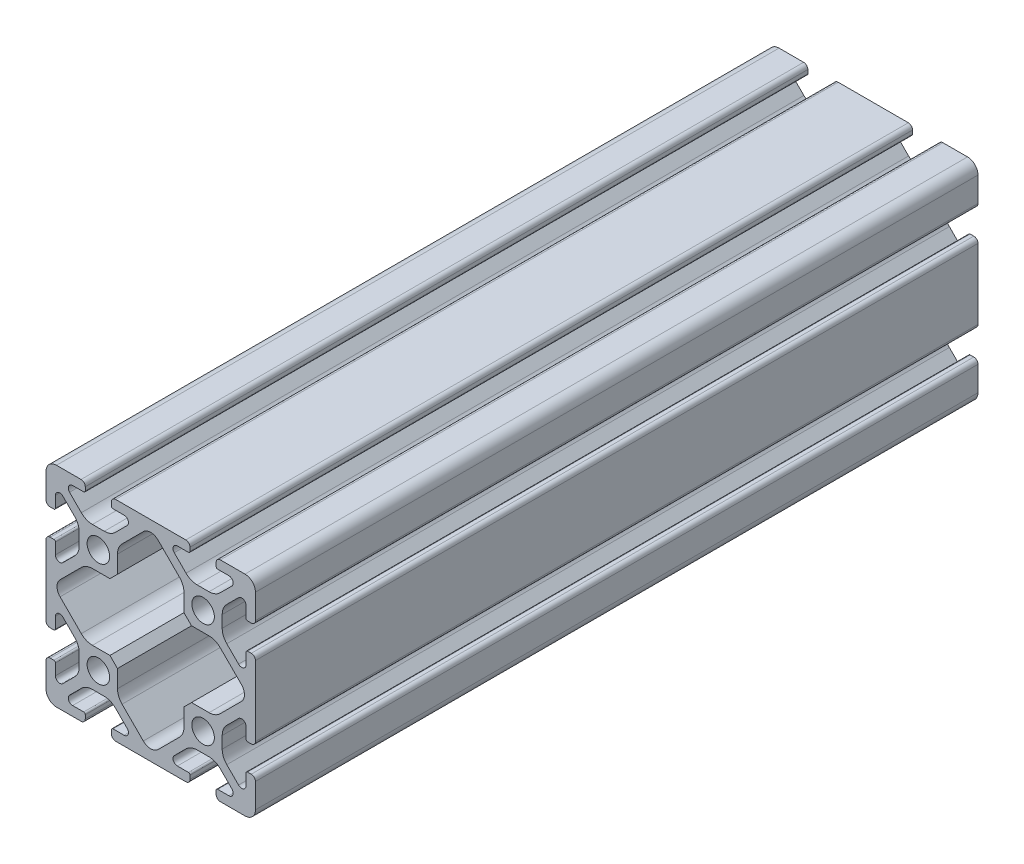
SolidWorks part; units mm, degrees
material "Alliage 1060"
ref_plane "Plan de face" through (0, 0, 0) normal (0, 0, 1) x (1, 0, 0)
ref_plane "Plan de dessus" through (0, 0, 0) normal (0, 1, 0) x (1, 0, 0)
ref_plane "Plan de droite" through (0, 0, 0) normal (1, 0, 0) x (0, 0, -1)
ref_plane "Plan1" through (0, 0, 0) normal (0, 0, -1) x (-1, 0, 0)
sketch "Esquisse1" plane through (0, 0, 0) normal (0, 0, -1) x (-1, 0, 0)
  line L0 (0, 13.3) -> (0, 26.7)
  line L1 (-0.8, 27.5) -> (-1.5, 27.5)
  line L2 (-1.8, 27.2) -> (-1.8, 25.0816)
  line L3 (-3.2196, 24.4936) -> (-5.4713, 26.7453)
  line L4 (-6.35, 28.8666) -> (-6.35, 31.1334)
  line L5 (-5.4713, 33.2547) -> (-3.2196, 35.5064)
  line L6 (-1.8, 34.9184) -> (-1.8, 32.8)
  line L7 (-1.5, 32.5) -> (-0.8, 32.5)
  line L8 (0, 33.3) -> (0, 38)
  line L9 (-2, 40) -> (-6.7, 40)
  line L10 (-7.5, 39.2) -> (-7.5, 38.5)
  line L11 (-7.2, 38.2) -> (-5.0816, 38.2)
  line L12 (-4.4936, 36.7804) -> (-6.7453, 34.5287)
  line L13 (-8.8666, 33.65) -> (-11.1334, 33.65)
  line L14 (-13.2547, 34.5287) -> (-15.5064, 36.7804)
  line L15 (-14.9184, 38.2) -> (-12.8, 38.2)
  line L16 (-12.5, 38.5) -> (-12.5, 39.2)
  line L17 (-13.3, 40) -> (-26.7, 40)
  line L18 (-27.5, 39.2) -> (-27.5, 38.5)
  line L19 (-27.2, 38.2) -> (-25.0816, 38.2)
  line L20 (-24.4936, 36.7804) -> (-26.7453, 34.5287)
  line L21 (-28.8666, 33.65) -> (-31.1334, 33.65)
  line L22 (-33.2547, 34.5287) -> (-35.5064, 36.7804)
  line L23 (-34.9184, 38.2) -> (-32.8, 38.2)
  line L24 (-32.5, 38.5) -> (-32.5, 39.2)
  line L25 (-33.3, 40) -> (-38, 40)
  line L26 (-40, 38) -> (-40, 33.3)
  line L27 (-39.2, 32.5) -> (-38.5, 32.5)
  line L28 (-38.2, 32.8) -> (-38.2, 34.9184)
  line L29 (-36.7804, 35.5064) -> (-34.5287, 33.2547)
  line L30 (-33.65, 31.1334) -> (-33.65, 28.8666)
  line L31 (-34.5287, 26.7453) -> (-36.7804, 24.4936)
  line L32 (-38.2, 25.0816) -> (-38.2, 27.2)
  line L33 (-38.5, 27.5) -> (-39.2, 27.5)
  line L34 (-40, 26.7) -> (-40, 13.3)
  line L35 (-39.2, 12.5) -> (-38.5, 12.5)
  line L36 (-38.2, 12.8) -> (-38.2, 14.9184)
  line L37 (-36.7804, 15.5064) -> (-34.5287, 13.2547)
  line L38 (-33.65, 11.1334) -> (-33.65, 8.8666)
  line L39 (-34.5287, 6.7453) -> (-36.7804, 4.4936)
  line L40 (-38.2, 5.0816) -> (-38.2, 7.2)
  line L41 (-38.5, 7.5) -> (-39.2, 7.5)
  line L42 (-40, 6.7) -> (-40, 2)
  line L43 (-38, 0) -> (-33.3, 0)
  line L44 (-32.5, 0.8) -> (-32.5, 1.5)
  line L45 (-32.8, 1.8) -> (-34.9184, 1.8)
  line L46 (-35.5064, 3.2196) -> (-33.2547, 5.4713)
  line L47 (-31.1334, 6.35) -> (-28.8666, 6.35)
  line L48 (-26.7453, 5.4713) -> (-24.4936, 3.2196)
  line L49 (-25.0816, 1.8) -> (-27.2, 1.8)
  line L50 (-27.5, 1.5) -> (-27.5, 0.8)
  line L51 (-26.7, 0) -> (-13.3, 0)
  line L52 (-12.5, 0.8) -> (-12.5, 1.5)
  line L53 (-12.8, 1.8) -> (-14.9184, 1.8)
  line L54 (-15.5064, 3.2196) -> (-13.2547, 5.4713)
  line L55 (-11.1334, 6.35) -> (-8.8666, 6.35)
  line L56 (-6.7453, 5.4713) -> (-4.4936, 3.2196)
  line L57 (-5.0816, 1.8) -> (-7.2, 1.8)
  line L58 (-7.5, 1.5) -> (-7.5, 0.8)
  line L59 (-6.7, 0) -> (-2, 0)
  line L60 (0, 2) -> (0, 6.7)
  line L61 (-0.8, 7.5) -> (-1.5, 7.5)
  line L62 (-1.8, 7.2) -> (-1.8, 5.0816)
  line L63 (-3.2196, 4.4936) -> (-5.4713, 6.7453)
  line L64 (-6.35, 8.8666) -> (-6.35, 11.1334)
  line L65 (-5.4713, 13.2547) -> (-3.2196, 15.5064)
  line L66 (-1.8, 14.9184) -> (-1.8, 12.8)
  line L67 (-1.5, 12.5) -> (-0.8, 12.5)
  line L68 (-12.2079, 13.65) -> (-13.65, 12.2079)
  line L69 (-13.65, 12.2079) -> (-13.65, 8.8654)
  line L70 (-14.5287, 6.7441) -> (-18.5858, 2.687)
  line L71 (-21.4142, 2.687) -> (-25.4713, 6.7441)
  line L72 (-26.35, 8.8654) -> (-26.35, 12.2079)
  line L73 (-26.35, 12.2079) -> (-27.0711, 12.9289)
  line L74 (-27.0711, 12.9289) -> (-27.7921, 13.65)
  line L75 (-27.7921, 13.65) -> (-31.1346, 13.65)
  line L76 (-33.2559, 14.5287) -> (-37.313, 18.5858)
  line L77 (-37.313, 21.4142) -> (-33.2559, 25.4713)
  line L78 (-31.1346, 26.35) -> (-27.7921, 26.35)
  line L79 (-27.7921, 26.35) -> (-27.0711, 27.0711)
  line L80 (-27.0711, 27.0711) -> (-26.35, 27.7921)
  line L81 (-26.35, 27.7921) -> (-26.35, 31.1346)
  line L82 (-25.4713, 33.2559) -> (-21.4142, 37.313)
  line L83 (-18.5858, 37.313) -> (-14.5287, 33.2559)
  line L84 (-13.65, 31.1346) -> (-13.65, 27.7921)
  line L85 (-13.65, 27.7921) -> (-12.2079, 26.35)
  line L86 (-12.2079, 26.35) -> (-8.8654, 26.35)
  line L87 (-6.7441, 25.4713) -> (-2.687, 21.4142)
  line L88 (-2.687, 18.5858) -> (-6.7441, 14.5287)
  line L89 (-8.8654, 13.65) -> (-12.2079, 13.65)
  arc A0 (-0.8, 12.5) -> (0, 13.3) centre (-0.8, 13.3) ccw
  arc A1 (0, 26.7) -> (-0.8, 27.5) centre (-0.8, 26.7) ccw
  arc A2 (-1.5, 27.5) -> (-1.8, 27.2) centre (-1.5, 27.2) ccw
  arc A3 (-1.8, 25.0816) -> (-3.2196, 24.4936) centre (-2.6316, 25.0816) cw
  arc A4 (-5.4713, 26.7453) -> (-6.35, 28.8666) centre (-3.35, 28.8666) cw
  arc A5 (-6.35, 31.1334) -> (-5.4713, 33.2547) centre (-3.35, 31.1334) cw
  arc A6 (-3.2196, 35.5064) -> (-1.8, 34.9184) centre (-2.6316, 34.9184) cw
  arc A7 (-1.8, 32.8) -> (-1.5, 32.5) centre (-1.5, 32.8) ccw
  arc A8 (-0.8, 32.5) -> (0, 33.3) centre (-0.8, 33.3) ccw
  arc A9 (0, 38) -> (-2, 40) centre (-2, 38) ccw
  arc A10 (-6.7, 40) -> (-7.5, 39.2) centre (-6.7, 39.2) ccw
  arc A11 (-7.5, 38.5) -> (-7.2, 38.2) centre (-7.2, 38.5) ccw
  arc A12 (-5.0816, 38.2) -> (-4.4936, 36.7804) centre (-5.0816, 37.3684) cw
  arc A13 (-6.7453, 34.5287) -> (-8.8666, 33.65) centre (-8.8666, 36.65) cw
  arc A14 (-11.1334, 33.65) -> (-13.2547, 34.5287) centre (-11.1334, 36.65) cw
  arc A15 (-15.5064, 36.7804) -> (-14.9184, 38.2) centre (-14.9184, 37.3684) cw
  arc A16 (-12.8, 38.2) -> (-12.5, 38.5) centre (-12.8, 38.5) ccw
  arc A17 (-12.5, 39.2) -> (-13.3, 40) centre (-13.3, 39.2) ccw
  arc A18 (-26.7, 40) -> (-27.5, 39.2) centre (-26.7, 39.2) ccw
  arc A19 (-27.5, 38.5) -> (-27.2, 38.2) centre (-27.2, 38.5) ccw
  arc A20 (-25.0816, 38.2) -> (-24.4936, 36.7804) centre (-25.0816, 37.3684) cw
  arc A21 (-26.7453, 34.5287) -> (-28.8666, 33.65) centre (-28.8666, 36.65) cw
  arc A22 (-31.1334, 33.65) -> (-33.2547, 34.5287) centre (-31.1334, 36.65) cw
  arc A23 (-35.5064, 36.7804) -> (-34.9184, 38.2) centre (-34.9184, 37.3684) cw
  arc A24 (-32.8, 38.2) -> (-32.5, 38.5) centre (-32.8, 38.5) ccw
  arc A25 (-32.5, 39.2) -> (-33.3, 40) centre (-33.3, 39.2) ccw
  arc A26 (-38, 40) -> (-40, 38) centre (-38, 38) ccw
  arc A27 (-40, 33.3) -> (-39.2, 32.5) centre (-39.2, 33.3) ccw
  arc A28 (-38.5, 32.5) -> (-38.2, 32.8) centre (-38.5, 32.8) ccw
  arc A29 (-38.2, 34.9184) -> (-36.7804, 35.5064) centre (-37.3684, 34.9184) cw
  arc A30 (-34.5287, 33.2547) -> (-33.65, 31.1334) centre (-36.65, 31.1334) cw
  arc A31 (-33.65, 28.8666) -> (-34.5287, 26.7453) centre (-36.65, 28.8666) cw
  arc A32 (-36.7804, 24.4936) -> (-38.2, 25.0816) centre (-37.3684, 25.0816) cw
  arc A33 (-38.2, 27.2) -> (-38.5, 27.5) centre (-38.5, 27.2) ccw
  arc A34 (-39.2, 27.5) -> (-40, 26.7) centre (-39.2, 26.7) ccw
  arc A35 (-40, 13.3) -> (-39.2, 12.5) centre (-39.2, 13.3) ccw
  arc A36 (-38.5, 12.5) -> (-38.2, 12.8) centre (-38.5, 12.8) ccw
  arc A37 (-38.2, 14.9184) -> (-36.7804, 15.5064) centre (-37.3684, 14.9184) cw
  arc A38 (-34.5287, 13.2547) -> (-33.65, 11.1334) centre (-36.65, 11.1334) cw
  arc A39 (-33.65, 8.8666) -> (-34.5287, 6.7453) centre (-36.65, 8.8666) cw
  arc A40 (-36.7804, 4.4936) -> (-38.2, 5.0816) centre (-37.3684, 5.0816) cw
  arc A41 (-38.2, 7.2) -> (-38.5, 7.5) centre (-38.5, 7.2) ccw
  arc A42 (-39.2, 7.5) -> (-40, 6.7) centre (-39.2, 6.7) ccw
  arc A43 (-40, 2) -> (-38, 0) centre (-38, 2) ccw
  arc A44 (-33.3, 0) -> (-32.5, 0.8) centre (-33.3, 0.8) ccw
  arc A45 (-32.5, 1.5) -> (-32.8, 1.8) centre (-32.8, 1.5) ccw
  arc A46 (-34.9184, 1.8) -> (-35.5064, 3.2196) centre (-34.9184, 2.6316) cw
  arc A47 (-33.2547, 5.4713) -> (-31.1334, 6.35) centre (-31.1334, 3.35) cw
  arc A48 (-28.8666, 6.35) -> (-26.7453, 5.4713) centre (-28.8666, 3.35) cw
  arc A49 (-24.4936, 3.2196) -> (-25.0816, 1.8) centre (-25.0816, 2.6316) cw
  arc A50 (-27.2, 1.8) -> (-27.5, 1.5) centre (-27.2, 1.5) ccw
  arc A51 (-27.5, 0.8) -> (-26.7, 0) centre (-26.7, 0.8) ccw
  arc A52 (-13.3, 0) -> (-12.5, 0.8) centre (-13.3, 0.8) ccw
  arc A53 (-12.5, 1.5) -> (-12.8, 1.8) centre (-12.8, 1.5) ccw
  arc A54 (-14.9184, 1.8) -> (-15.5064, 3.2196) centre (-14.9184, 2.6316) cw
  arc A55 (-13.2547, 5.4713) -> (-11.1334, 6.35) centre (-11.1334, 3.35) cw
  arc A56 (-8.8666, 6.35) -> (-6.7453, 5.4713) centre (-8.8666, 3.35) cw
  arc A57 (-4.4936, 3.2196) -> (-5.0816, 1.8) centre (-5.0816, 2.6316) cw
  arc A58 (-7.2, 1.8) -> (-7.5, 1.5) centre (-7.2, 1.5) ccw
  arc A59 (-7.5, 0.8) -> (-6.7, 0) centre (-6.7, 0.8) ccw
  arc A60 (-2, 0) -> (0, 2) centre (-2, 2) ccw
  arc A61 (0, 6.7) -> (-0.8, 7.5) centre (-0.8, 6.7) ccw
  arc A62 (-1.5, 7.5) -> (-1.8, 7.2) centre (-1.5, 7.2) ccw
  arc A63 (-1.8, 5.0816) -> (-3.2196, 4.4936) centre (-2.6316, 5.0816) cw
  arc A64 (-5.4713, 6.7453) -> (-6.35, 8.8666) centre (-3.35, 8.8666) cw
  arc A65 (-6.35, 11.1334) -> (-5.4713, 13.2547) centre (-3.35, 11.1334) cw
  arc A66 (-3.2196, 15.5064) -> (-1.8, 14.9184) centre (-2.6316, 14.9184) cw
  arc A67 (-1.8, 12.8) -> (-1.5, 12.5) centre (-1.5, 12.8) ccw
  circle A68 centre (-10, 10) radius 2.15
  circle A69 centre (-10, 30) radius 2.15
  circle A70 centre (-30, 10) radius 2.15
  circle A71 centre (-30, 30) radius 2.15
  arc A72 (-13.65, 8.8654) -> (-14.5287, 6.7441) centre (-16.65, 8.8654) cw
  arc A73 (-18.5858, 2.687) -> (-21.4142, 2.687) centre (-20, 4.1012) cw
  arc A74 (-25.4713, 6.7441) -> (-26.35, 8.8654) centre (-23.35, 8.8654) cw
  arc A75 (-31.1346, 13.65) -> (-33.2559, 14.5287) centre (-31.1346, 16.65) cw
  arc A76 (-37.313, 18.5858) -> (-37.313, 21.4142) centre (-35.8988, 20) cw
  arc A77 (-33.2559, 25.4713) -> (-31.1346, 26.35) centre (-31.1346, 23.35) cw
  arc A78 (-26.35, 31.1346) -> (-25.4713, 33.2559) centre (-23.35, 31.1346) cw
  arc A79 (-21.4142, 37.313) -> (-18.5858, 37.313) centre (-20, 35.8988) cw
  arc A80 (-14.5287, 33.2559) -> (-13.65, 31.1346) centre (-16.65, 31.1346) cw
  arc A81 (-8.8654, 26.35) -> (-6.7441, 25.4713) centre (-8.8654, 23.35) cw
  arc A82 (-2.687, 21.4142) -> (-2.687, 18.5858) centre (-4.1012, 20) cw
  arc A83 (-6.7441, 14.5287) -> (-8.8654, 13.65) centre (-8.8654, 16.65) cw
extrude "Extrusion1" add sketch "Esquisse1" against normal blind 138
